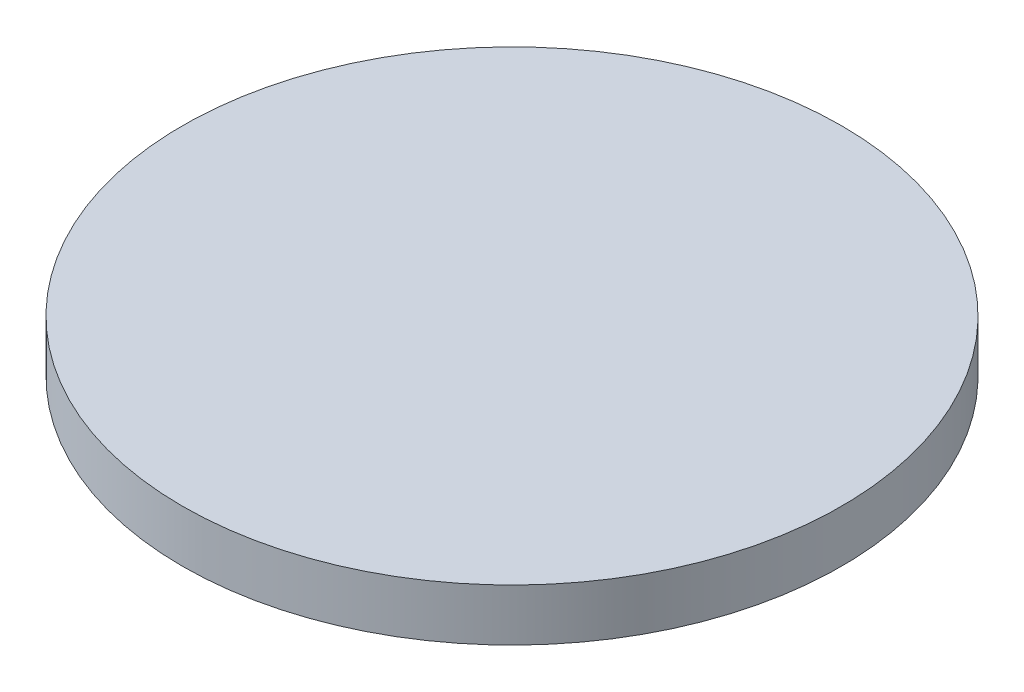
SolidWorks part; units mm, degrees
ref_plane "Front Plane" through (0, 0, 0) normal (0, 0, 1) x (1, 0, 0)
ref_plane "Top Plane" through (0, 0, 0) normal (0, 1, 0) x (1, 0, 0)
ref_plane "Right Plane" through (0, 0, 0) normal (1, 0, 0) x (0, 0, -1)
sketch "Sketch1" plane through (0, 0, 0) normal (0, 1, 0) x (1, 0, 0)
  circle A0 centre (0, 0) radius 19
  dimension "D1" = 38
extrude "Boss-Extrude1" add sketch "Sketch1" along normal blind 3 separate body
equation "\"D1@Sketch1\"=19*2"
